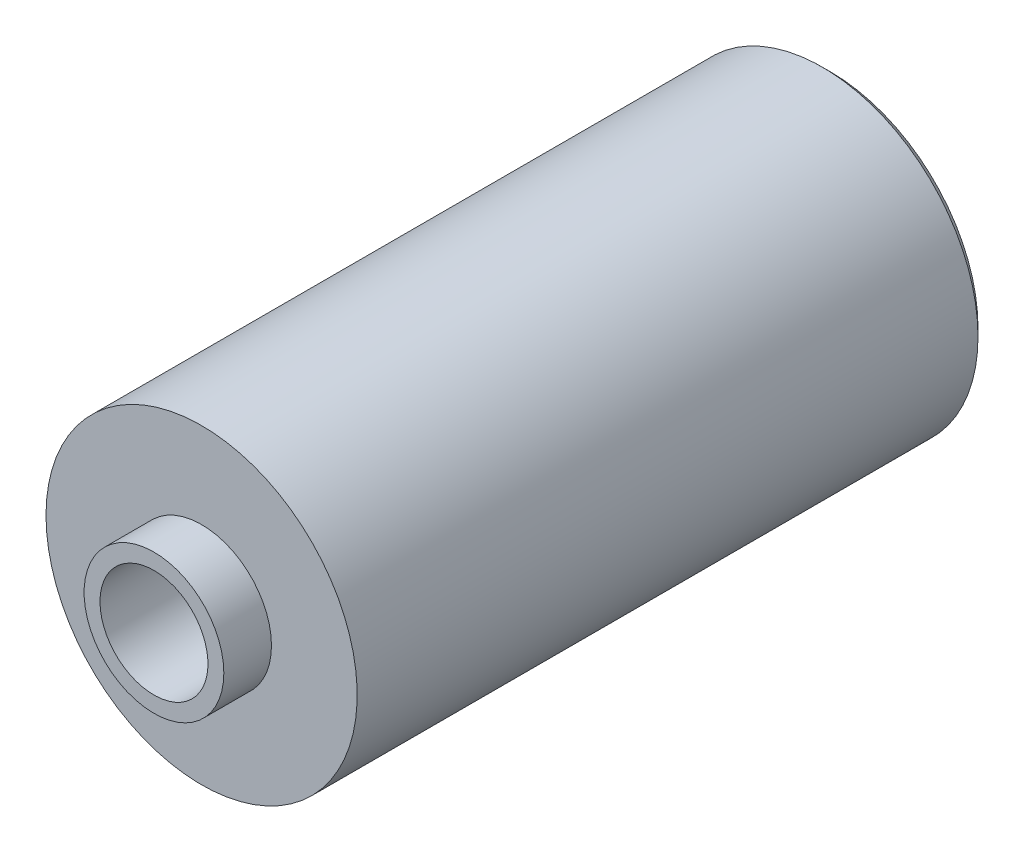
SolidWorks part; units mm, degrees
ref_plane "Front Plane" through (0, 0, 0) normal (0, 0, 1) x (1, 0, 0)
ref_plane "Top Plane" through (0, 0, 0) normal (0, 1, 0) x (1, 0, 0)
ref_plane "Right Plane" through (0, 0, 0) normal (1, 0, 0) x (0, 0, -1)
sketch "Sketch1" plane through (0, 0, 0) normal (0, 0, 1) x (1, 0, 0)
  circle A0 centre (0, 0) radius 1.7
  circle A2 centre (0, 0) radius 4.9
  dimension "D1" = 3.4
  dimension "D2" = 9.8
extrude "Boss-Extrude1" add sketch "Sketch1" along normal blind 19.8
sketch "Sketch2" plane through (0, 0, 19.8) normal (0, 0, 1) x (1, 0, 0)
  circle A0 centre (0, 0) radius 1.7
  circle A2 centre (0, 0) radius 2.2
  dimension "D1" = 3.4
  dimension "D2" = 0.5
extrude "Boss-Extrude2" add sketch "Sketch2" along normal blind 1.5
sketch "Sketch3" plane through (0, 0, 0) normal (0, 0, 1) x (1, 0, 0)
  circle A0 centre (0, 0) radius 2.2
  circle A1 centre (0, 0) radius 1.7
  dimension "D1" = 4.4
  dimension "D2" = 3.4
chamfer "Chamfer1" distance 0.25 angle 45 2 edges at (1.7, 0, 0) (4.9, 0, 0)
